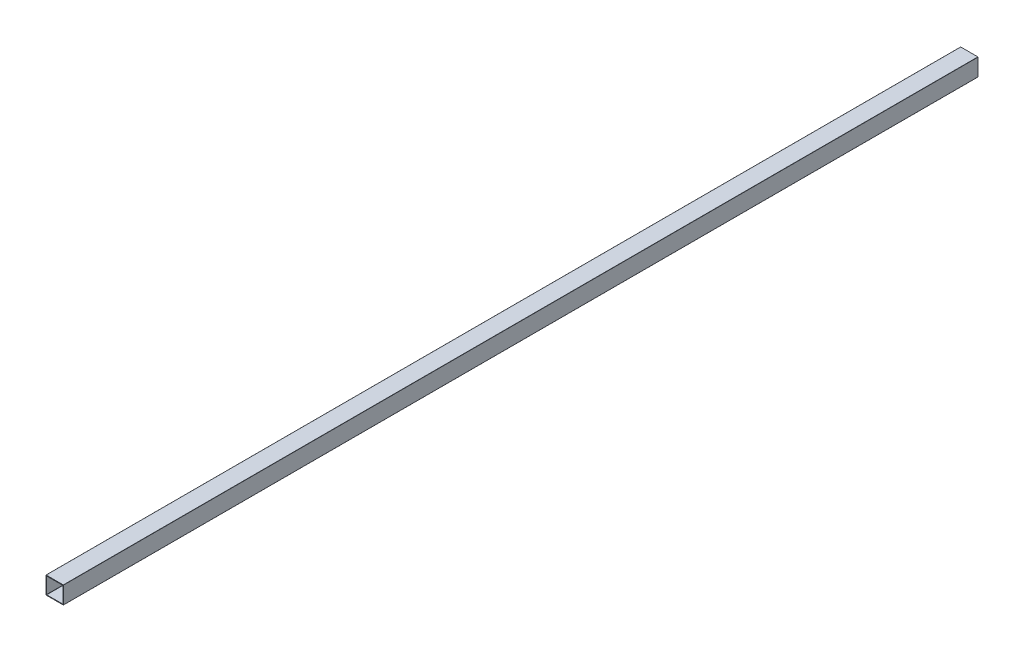
SolidWorks part; units mm, degrees
material "AISI 1035 Acero (SS)"
ref_plane "Alzado" through (0, 0, 0) normal (0, 0, 1) x (1, 0, 0)
ref_plane "Planta" through (0, 0, 0) normal (0, 1, 0) x (1, 0, 0)
ref_plane "Vista lateral" through (0, 0, 0) normal (1, 0, 0) x (0, 0, -1)
sketch "Croquis1" plane through (0, 0, 0) normal (0, 0, 1) x (1, 0, 0)
  line L0 (-53.35, -53.35) -> (-53.35, 53.35)
  line L1 (-57.15, -57.15) -> (57.15, -57.15)
  line L2 (-57.15, -57.15) -> (-57.15, 57.15)
  line L3 (-57.15, 57.15) -> (57.15, 57.15)
  line L4 (57.15, -57.15) -> (57.15, 57.15)
  line L5 (-57.15, -57.15) -> (57.15, 57.15) construction
  line L6 (-57.15, 57.15) -> (57.15, -57.15) construction
  line L7 (-53.35, 53.35) -> (53.35, 53.35)
  line L8 (53.35, -53.35) -> (53.35, 53.35)
  line L9 (-53.35, -53.35) -> (53.35, -53.35)
  point P0 (0, 0)
  dimension "D2" = 114.3
  dimension "D3" = 3.8
extrude "Saliente-Extruir1" add sketch "Croquis1" against normal blind 6000
fillet "Redondeo1" radius 1 8 edges at (-53.35, 53.35, -3000) (53.35, 53.35, -3000) (53.35, -53.35, -3000) (-57.15, -57.15, -3000) (-57.15, 57.15, -3000) (-53.35, -53.35, -3000) (57.15, -57.15, -3000) (57.15, 57.15, -3000)
